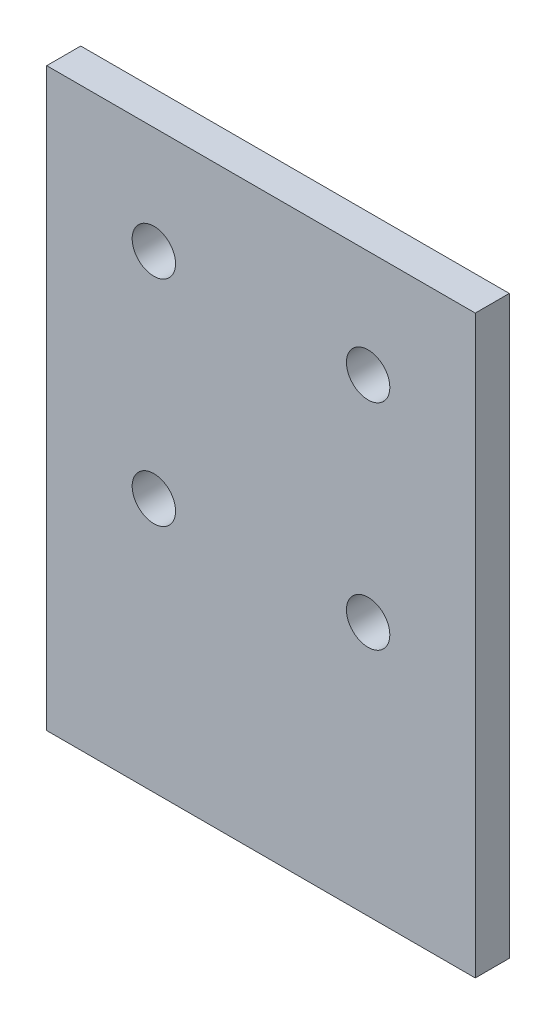
SolidWorks part; units mm, degrees
material "AISI Type A2 Tool Steel"
ref_plane "Front Plane" through (0, 0, 0) normal (0, 0, 1) x (1, 0, 0)
ref_plane "Top Plane" through (0, 0, 0) normal (0, 1, 0) x (1, 0, 0)
ref_plane "Right Plane" through (0, 0, 0) normal (1, 0, 0) x (0, 0, -1)
sketch "Sketch1" plane through (0, 0, 0) normal (0, 0, 1) x (1, 0, 0)
  line L0 (0, 0) -> (0, 40) construction
  line L1 (-20, 20) -> (20, 20) construction
  line L2 (-20, 20) -> (-20, -20) construction
  line L3 (-20, -20) -> (20, -20) construction
  line L4 (20, 20) -> (20, -20) construction
  line L5 (-20, 20) -> (20, -20) construction
  line L6 (-20, -20) -> (20, 20) construction
  line L7 (-40, 40) -> (40, 40)
  line L8 (-40, 40) -> (-40, -67.5)
  line L9 (-40, -67.5) -> (40, -67.5)
  line L10 (40, 40) -> (40, -67.5)
  line L11 (-40, -27.5) -> (40, -27.5) construction
  circle A0 centre (-20, 20) radius 4.05
  circle A1 centre (20, 20) radius 4.05
  circle A2 centre (20, -20) radius 4.05
  circle A3 centre (-20, -20) radius 4.05
  circle A4 centre (-20, -20) radius 7.5 construction
  point P0 (0, 0)
  dimension "D2" = 8.1
  dimension "D6" = 15
  dimension "D1" = 40
  dimension "D3" = 80
  dimension "D4" = 20
  dimension "D5" = 40
extrude "Boss-Extrude1" add sketch "Sketch1" along normal blind 6.35
